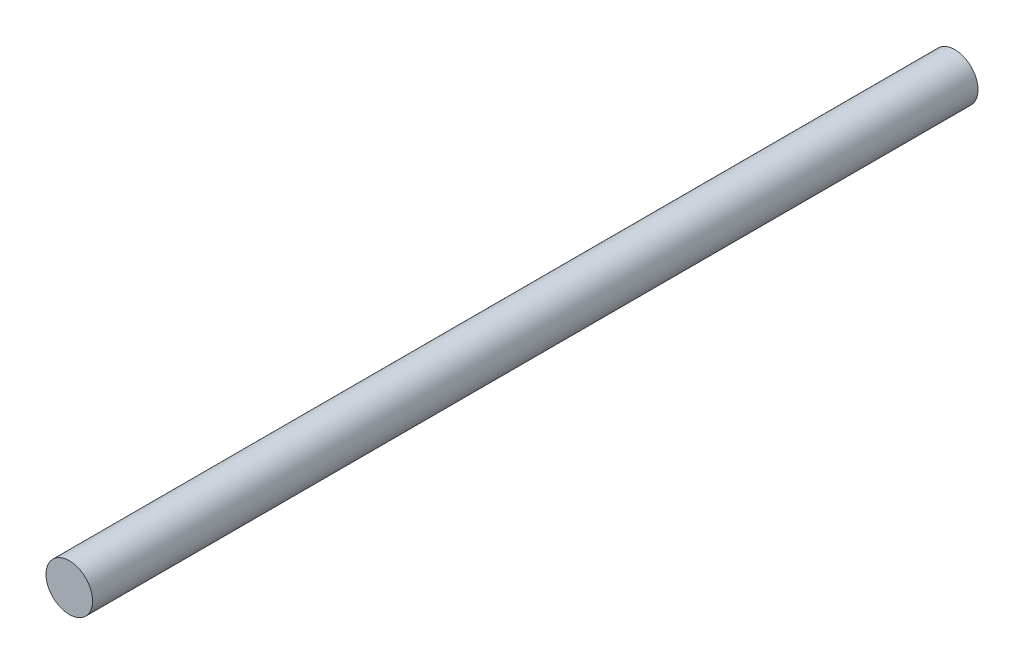
SolidWorks part; units mm, degrees
material "Plain Carbon Steel"
ref_plane "Front Plane" through (0, 0, 0) normal (0, 0, 1) x (1, 0, 0)
ref_plane "Top Plane" through (0, 0, 0) normal (0, 1, 0) x (1, 0, 0)
ref_plane "Right Plane" through (0, 0, 0) normal (1, 0, 0) x (0, 0, -1)
sketch "Sketch1" plane through (0, 0, 0) normal (0, 0, 1) x (1, 0, 0)
  circle A0 centre (0, 0) radius 6.35
  dimension "D1" = 12.7
extrude "Boss-Extrude1" add sketch "Sketch1" along normal blind 241.3
